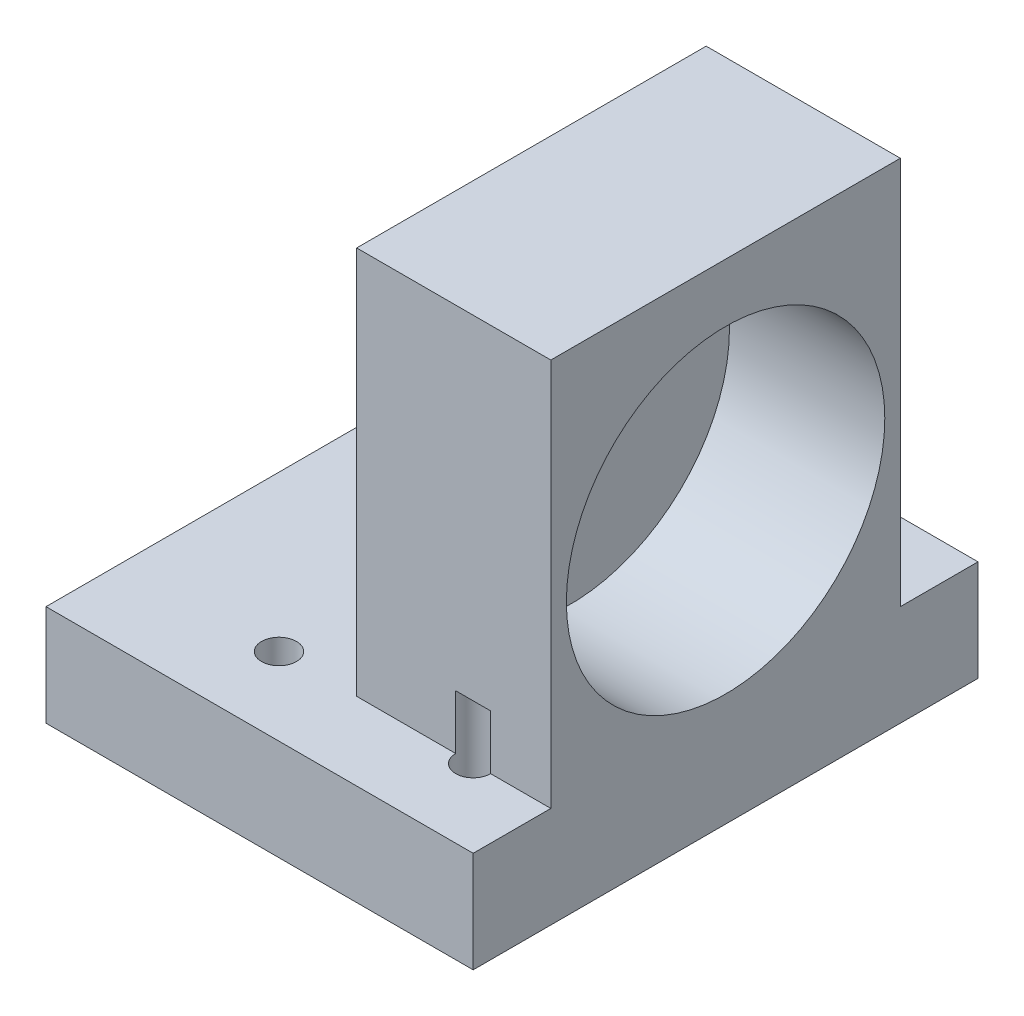
SolidWorks part; units mm, degrees
ref_plane "Front Plane" through (0, 0, 0) normal (0, 0, 1) x (1, 0, 0)
ref_plane "Top Plane" through (0, 0, 0) normal (0, 1, 0) x (1, 0, 0)
ref_plane "Right Plane" through (0, 0, 0) normal (1, 0, 0) x (0, 0, -1)
sketch "Sketch1" plane through (0, 0, 0) normal (0, 1, 0) x (1, 0, 0)
  line L1 (-32.5, 32.5) -> (22.5, 32.5)
  line L2 (-32.5, 32.5) -> (-32.5, -32.5)
  line L3 (-32.5, -32.5) -> (22.5, -32.5)
  line L4 (22.5, 32.5) -> (22.5, -32.5)
  dimension "D1" = 55
  dimension "D2" = 65
  dimension "D3" = 32.5
  dimension "D4" = 22.5
extrude "Boss-Extrude1" add sketch "Sketch1" along normal blind 13
sketch "Sketch2" plane through (0, 13, 0) normal (0, 1, 0) x (1, 0, 0)
  line L0 (22.5, -32.5) -> (22.5, 32.5) construction
  line L1 (22.5, 22.5) -> (-2.5, 22.5)
  line L2 (22.5, 22.5) -> (22.5, -22.5)
  line L3 (22.5, -22.5) -> (-2.5, -22.5)
  line L4 (-2.5, 22.5) -> (-2.5, -22.5)
  dimension "D1" = 45
  dimension "D2" = 22.5
  dimension "D3" = 25
extrude "Boss-Extrude2" add sketch "Sketch2" along normal blind 50
sketch "Sketch5" plane through (22.5, 0, 0) normal (1, 0, 0) x (0, 0, -1)
  circle A0 centre (0, 35) radius 20.5
  dimension "D1" = 41
  dimension "D2" = 35
extrude "Cut-Extrude1" cut sketch "Sketch5" against normal blind 20
sketch "Sketch7" plane through (2.5, 0, 0) normal (1, 0, 0) x (0, 0, -1)
  circle A0 centre (0, 35) radius 7
  dimension "D1" = 14
  dimension "D2" = 35
extrude "Cut-Extrude2" cut sketch "Sketch7" against normal blind 20
sketch "Sketch8" plane through (0, 0, 0) normal (0, -1, 0) x (-1, 0, 0)
  line L0 (32.5, 32.5) -> (32.5, -32.5) construction
  circle A0 centre (12.5, -22.5) radius 2.25
  circle A1 centre (12.5, 22.5) radius 2.25
  circle A2 centre (-12.5, 22.5) radius 2.25
  circle A3 centre (-12.5, -22.5) radius 2.25
  dimension "D1" = 4.5
  dimension "D2" = 4.5
  dimension "D3" = 4.5
  dimension "D4" = 4.5
  dimension "D5" = 25
  dimension "D6" = 22.5
  dimension "D7" = 22.5
  dimension "D8" = 22.5
  dimension "D9" = 22.5
  dimension "D10" = 20
  dimension "D11" = 20
  dimension "D12" = 25
extrude "Cut-Extrude3" cut sketch "Sketch8" against normal blind 20
fillet "Fillet1" radius 10 1 edges at (-32.5, 6.5, -32.5)
